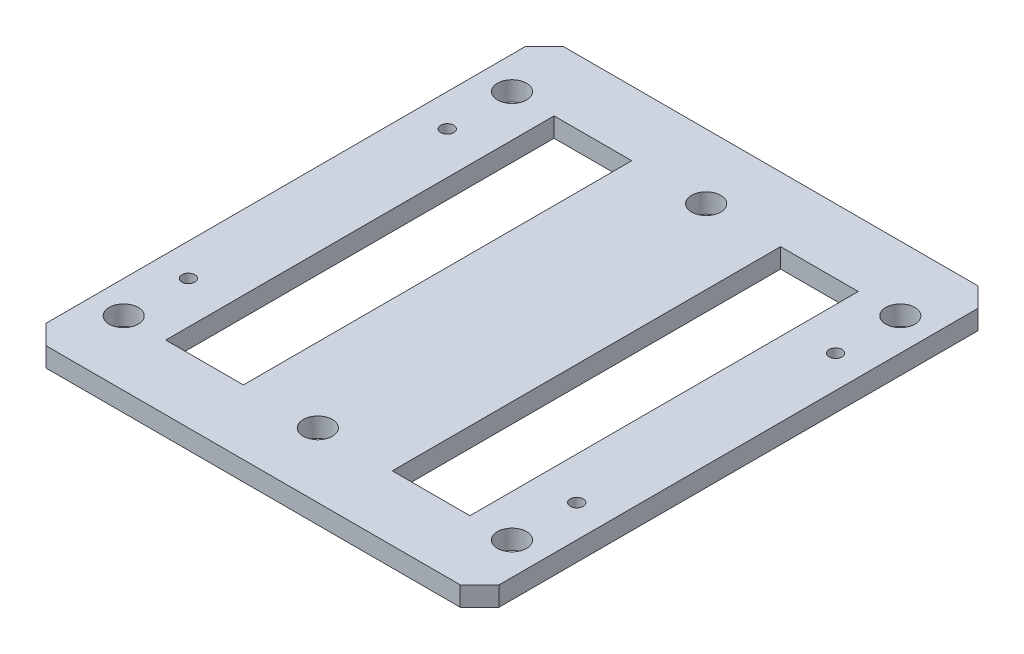
SolidWorks part; units mm, degrees
ref_plane "Plan de face" through (0, 0, 0) normal (0, 0, 1) x (1, 0, 0)
ref_plane "Plan de dessus" through (0, 0, 0) normal (0, 1, 0) x (1, 0, 0)
ref_plane "Plan de droite" through (0, 0, 0) normal (1, 0, 0) x (0, 0, -1)
sketch "Esquisse1" plane through (0, 0, 0) normal (0, 0, 1) x (1, 0, 0)
  line L1 (0, 0) -> (70, 0)
  line L2 (0, 0) -> (0, 12)
  line L3 (0, 12) -> (70, 12)
  line L4 (70, 0) -> (70, 12)
  dimension "D1" = 12
  dimension "D2" = 70
extrude "Boss.-Extru.1" add sketch "Esquisse1" along normal blind 80
sketch "Esquisse2" plane through (0, 0, 80) normal (0, 0, 1) x (1, 0, 0)
  line L0 (35, 0) -> (35, 12) construction
  line L1 (0, 0) -> (70, 0) construction
  line L2 (70, 12) -> (0, 12) construction
  line L3 (58.5, 12) -> (58.5, 6)
  line L4 (23.5, 12) -> (11.5, 12)
  line L5 (23.5, 12) -> (23.5, 6)
  line L6 (23.5, 6) -> (11.5, 6)
  line L7 (11.5, 12) -> (11.5, 6)
  line L8 (46.5, 6) -> (58.5, 6)
  line L9 (46.5, 12) -> (46.5, 6)
  line L10 (46.5, 12) -> (58.5, 12)
  dimension "D1" = 12
  dimension "D2" = 6
  dimension "D3" = 23
extrude "Enlèv. mat.-Extru.1" cut sketch "Esquisse2" against normal through all
sketch "Esquisse4" plane through (0, 12, 0) normal (0, 1, 0) x (1, 0, 0)
  line L0 (0, -10) -> (70, -10) construction
  line L1 (0, -80) -> (0, 0) construction
  line L3 (0, -40) -> (70, -40) construction
  line L4 (70, -80) -> (70, 0) construction
  line L5 (46.5, 0) -> (23.5, 0) construction
  line L6 (0, -70) -> (70, -70) construction
  line L8 (35, -10) -> (35, -70) construction
  circle A0 centre (5, -10) radius 2.25
  circle A1 centre (65, -70) radius 2.25
  circle A2 centre (65, -10) radius 2.25
  circle A3 centre (5, -70) radius 2.25
  circle A4 centre (35, -10) radius 2.25
  circle A5 centre (35, -70) radius 2.25
  dimension "D1" = 4.5
  dimension "D2" = 30
  dimension "D4" = 10
extrude "Enlèv. mat.-Extru.3" cut sketch "Esquisse4" against normal through all
sketch "Esquisse5" plane through (0, 12, 0) normal (0, 1, 0) x (1, 0, 0)
  line L0 (23.5, 0) -> (23.5, -80) construction
  line L1 (11.5, -80) -> (23.5, -80)
  line L2 (11.5, -80) -> (11.5, -70)
  line L3 (11.5, -70) -> (23.5, -70)
  line L4 (23.5, -80) -> (23.5, -70)
  line L5 (35, -80) -> (35, 0) construction
  line L6 (46.5, -80) -> (23.5, -80) construction
  line L7 (46.5, 0) -> (23.5, 0) construction
  line L8 (70, -40) -> (0, -40) construction
  line L9 (70, -80) -> (70, 0) construction
  line L10 (0, -80) -> (0, 0) construction
  line L11 (46.5, -80) -> (46.5, -70)
  line L12 (58.5, -70) -> (46.5, -70)
  line L13 (58.5, -80) -> (58.5, -70)
  line L14 (58.5, -80) -> (46.5, -80)
  line L15 (58.5, 0) -> (46.5, 0)
  line L16 (58.5, 0) -> (58.5, -10)
  line L17 (58.5, -10) -> (46.5, -10)
  line L18 (46.5, 0) -> (46.5, -10)
  line L19 (23.5, 0) -> (23.5, -10)
  line L20 (11.5, -10) -> (23.5, -10)
  line L21 (11.5, 0) -> (11.5, -10)
  line L22 (11.5, 0) -> (23.5, 0)
  dimension "D1" = 10
extrude "Boss.-Extru.2" add sketch "Esquisse5" against normal up to vertex (6 mm away) up to point (46.5, 6, 0)
chamfer "Chanfrein1" distance 3 angle 45 4 edges at (0, 6, 0) (0, 6, 80) (70, 6, 0) (70, 6, 80)
sketch "Esquisse6" plane through (0, 12, 0) normal (0, 1, 0) x (1, 0, 0)
  line L0 (35, -80) -> (35, 0) construction
  line L1 (67, -80) -> (3, -80) construction
  line L2 (67, 0) -> (3, 0) construction
  line L3 (5, -20) -> (35, -20) construction
  line L4 (0, -40) -> (35, -40) construction
  line L5 (0, -77) -> (0, -3) construction
  line L6 (5, -20) -> (5, -40) construction
  line L7 (65, -20) -> (65, -40) construction
  circle A0 centre (5, -20) radius 1
  circle A1 centre (5, -60) radius 1
  circle A2 centre (65, -60) radius 1
  circle A3 centre (65, -20) radius 1
  dimension "D2" = 2
  dimension "D1" = 30
  dimension "D3" = 20
extrude "Enlèv. mat.-Extru.4" cut sketch "Esquisse6" against normal up to vertex (12 mm away) up to point (70, 0, 3)
sketch "Esquisse8" plane through (0, 0, 80) normal (0, 0, 1) x (1, 0, 0)
  line L0 (70, 12) -> (70, 0) construction
  line L1 (0, 0) -> (70, 0)
  line L2 (0, 0) -> (0, 9)
  line L3 (0, 9) -> (70, 9)
  line L4 (70, 0) -> (70, 9)
  dimension "D1" = 3
extrude "Enlèv. mat.-Extru.8" cut sketch "Esquisse8" against normal up to vertex
